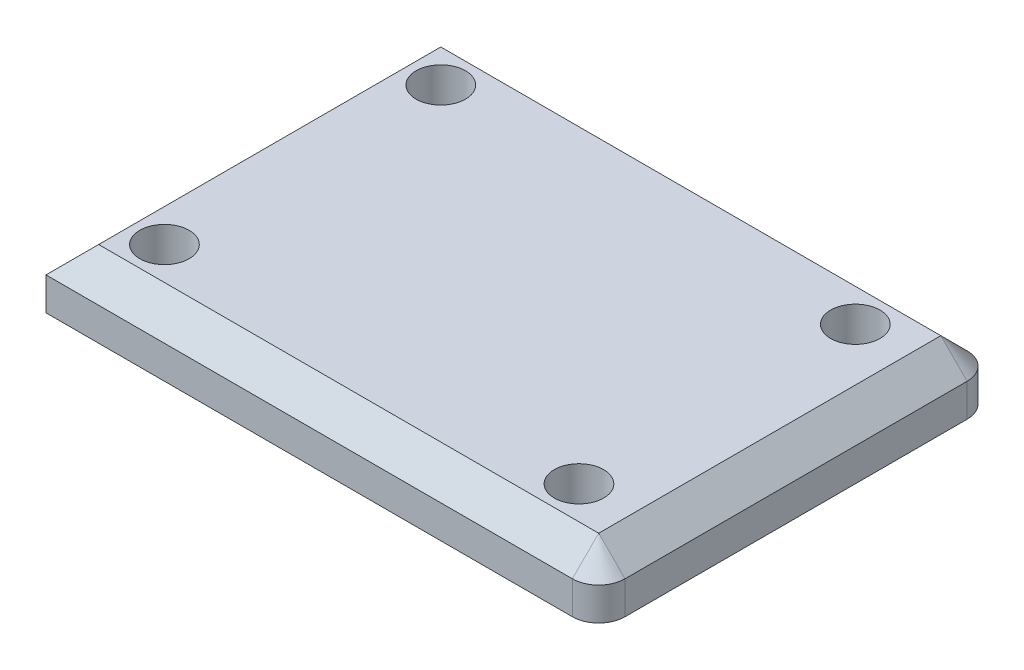
SolidWorks part; units mm, degrees
ref_plane "Ön Düzlem" through (0, 0, 0) normal (0, 0, 1) x (1, 0, 0)
ref_plane "Üst Düzlem" through (0, 0, 0) normal (0, 1, 0) x (1, 0, 0)
ref_plane "Sağ Düzlem" through (0, 0, 0) normal (1, 0, 0) x (0, 0, -1)
sketch "Sketch1" plane through (0, 0, 0) normal (0, 1, 0) x (1, 0, 0)
  line L1 (14, -10) -> (-14, -10)
  line L2 (14, -10) -> (14, 10)
  line L3 (14, 10) -> (-14, 10)
  line L4 (-14, -10) -> (-14, 10)
  line L5 (14, -10) -> (-14, 10) construction
  line L6 (14, 10) -> (-14, -10) construction
  point P0 (0, 0)
  dimension "D1" = 20
  dimension "D2" = 28
extrude "Boss-Extrude1" add sketch "Sketch1" along normal blind 3
hole_wizard "M3 Tapped Hole1" positions "Sketch2" profile "Sketch3" tap size "M3" standard "DIN" end condition through all
sketch "Sketch2" plane through (0, 3, 0) normal (0, 1, 0) x (1, 0, 0)
  line L0 (-14, 10) -> (-14, -10) construction
  line L1 (14, 10) -> (-14, 10) construction
  point P0 (-11, 7)
  point P2 (-11, -7)
  point P4 (10, -7)
  point P6 (10, 7)
  dimension "D1" = 14
  dimension "D2" = 21
  dimension "D3" = 3
  dimension "D4" = 3
sketch "Sketch3" plane through (-11, 3, -7) normal (1, 0, 0) x (0, 0, 1)
  line L0 (0, 0) -> (0, 3)
  line L1 (0, 3) -> (1.25, 3)
  line L2 (1.25, 3) -> (1.25, 0)
  line L5 (1.25, 0) -> (0, 0)
  line L11 (0, -6.35) -> (0, 107.95) construction
  dimension "Thru Tap Drill Dia." = 2.5
  dimension "Thru Tap Drill Depth" = 3
cosmetic thread "Hole Thread1" parameters "D2"=3
cosmetic thread "Hole Thread2" parameters "D2"=3
cosmetic thread "Hole Thread3" parameters "D2"=3
cosmetic thread "Hole Thread4" parameters "D2"=3
scale "Scale1" scale about centroid uniform scaling yes scale factor 1.5
fillet "Fillet1" radius 2 2 edges at (20.9909, 1.5, 15) (20.9909, 1.5, -15)
chamfer "Chamfer1" distance 2 angle 45 6 edges at (-1.0091, 3.75, 15) (20.4051, 3.75, 14.4142) (20.9909, 3.75, 0) (20.4051, 3.75, -14.4142) (-1.0091, 3.75, -15) (-21.0091, 3.75, 0)
